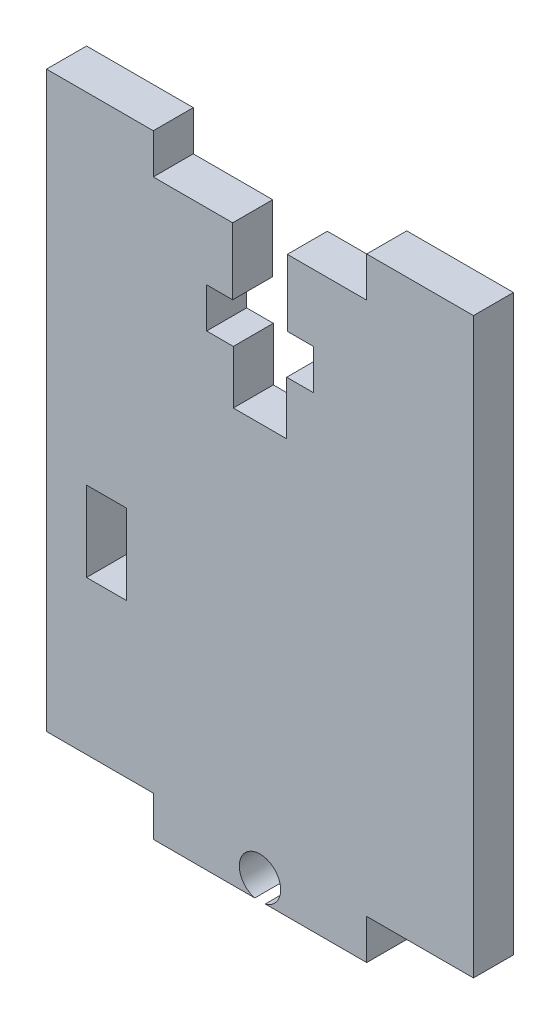
SolidWorks part; units mm, degrees
ref_plane "前视" through (0, 0, 0) normal (0, 0, 1) x (1, 0, 0)
ref_plane "上视" through (0, 0, 0) normal (0, 1, 0) x (1, 0, 0)
ref_plane "右视" through (0, 0, 0) normal (1, 0, 0) x (0, 0, -1)
sketch "草图2" plane through (0, 0, 0) normal (0, 0, 1) x (1, 0, 0)
  line L0 (0, 103.0974) -> (0, -63.3868) construction
  line L1 (2.0479, 48.8553) -> (8, 48.8553)
  line L2 (8, 48.8553) -> (8, 51.8553)
  line L3 (8, 51.8553) -> (16, 51.8553)
  line L4 (16, 51.8553) -> (16, 8.8553)
  line L5 (16, 8.8553) -> (8, 8.8553)
  line L6 (2.0479, 48.8553) -> (2.0479, 43.8553)
  line L7 (2.0479, 43.8553) -> (4, 43.8553)
  line L8 (4, 43.8553) -> (4, 40.8553)
  line L9 (4, 40.8553) -> (2, 40.8553)
  line L10 (2, 40.8553) -> (2, 36.8553)
  line L11 (2, 36.8553) -> (-2, 36.8553)
  line L12 (-8, 5.8553) -> (-0.3905, 5.8553)
  line L13 (8, 5.8553) -> (8, 8.8553)
  line L14 (-8, 5.8553) -> (-8, 8.8553)
  line L15 (0.3905, 5.8553) -> (8, 5.8553)
  line L16 (-2, 40.8553) -> (-2, 36.8553)
  line L17 (-4, 40.8553) -> (-2, 40.8553)
  line L18 (-4, 43.8553) -> (-4, 40.8553)
  line L19 (-2.0479, 43.8553) -> (-4, 43.8553)
  line L20 (-2.0479, 48.8553) -> (-2.0479, 43.8553)
  line L21 (-16, 8.8553) -> (-8, 8.8553)
  line L22 (-16, 51.8553) -> (-16, 8.8553)
  line L23 (-8, 51.8553) -> (-16, 51.8553)
  line L24 (-8, 48.8553) -> (-8, 51.8553)
  line L25 (-2.0479, 48.8553) -> (-8, 48.8553)
  line L27 (-13, 20.3553) -> (-10, 20.3553)
  line L28 (-13, 20.3553) -> (-13, 26.3553)
  line L29 (-13, 26.3553) -> (-10, 26.3553)
  line L30 (-10, 20.3553) -> (-10, 26.3553)
  arc A0 (0.3905, 5.8553) -> (-0.3905, 5.8553) centre (0, 7.3553) ccw
  point P22 (0, 36.8553)
  dimension "D12" = 1.5
  dimension "D11" = 3.1
  dimension "D1" = 8
  dimension "D2" = 8
  dimension "D3" = 3
  dimension "D4" = 12
  dimension "D5" = 5
  dimension "D6" = 3
  dimension "D7" = 2
  dimension "D8" = 2
  dimension "D9" = 40
  dimension "D10" = 3
  dimension "D13" = 3
  dimension "D14" = 6
  dimension "D15" = 3
  dimension "D16" = 11.5
extrude "凸台-拉伸1" add sketch "草图2" along normal blind 3
